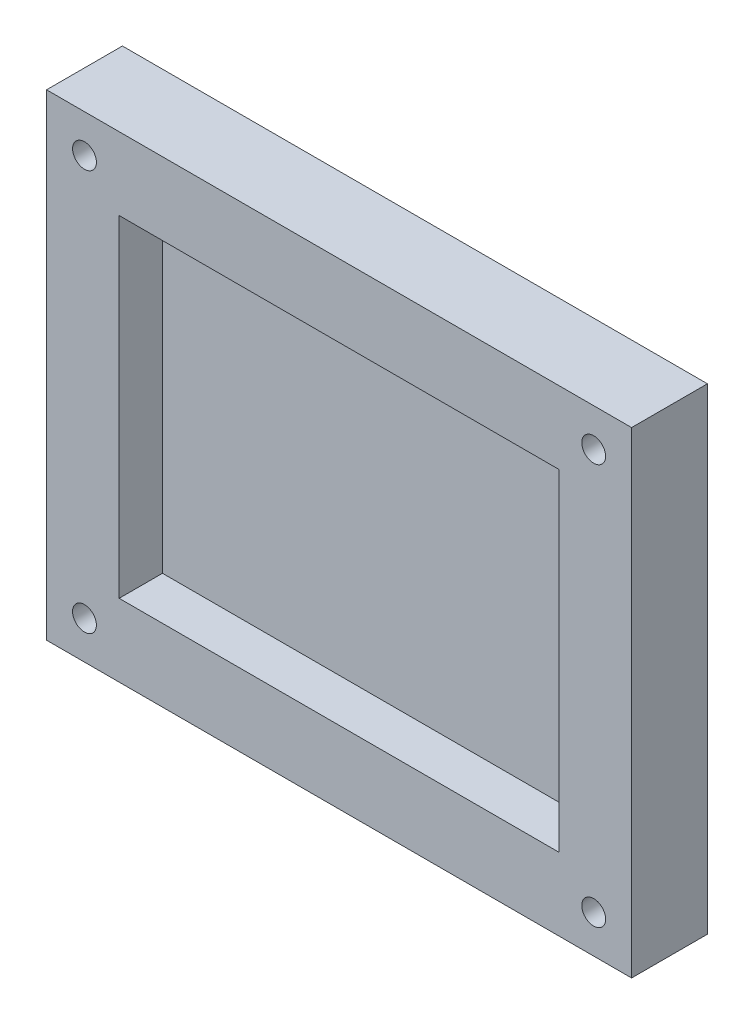
SolidWorks part; units mm, degrees
ref_plane "Front Plane" through (0, 0, 0) normal (0, 0, 1) x (1, 0, 0)
ref_plane "Top Plane" through (0, 0, 0) normal (0, 1, 0) x (1, 0, 0)
ref_plane "Right Plane" through (0, 0, 0) normal (1, 0, 0) x (0, 0, -1)
other "Configuration Table"
sketch "Sketch2" plane through (0, 0, 0) normal (0, 0, 1) x (1, 0, 0)
  line L1 (-54, -44) -> (54, -44)
  line L2 (-54, -44) -> (-54, 44)
  line L3 (-54, 44) -> (54, 44)
  line L4 (54, -44) -> (54, 44)
extrude "Fixture_floor" add sketch "Sketch2" along normal blind 6 from offset 0
sketch "Sketch3" plane through (0, 0, 0) normal (0, 0, 1) x (1, 0, 0)
  line L1 (-54, -44) -> (54, -44)
  line L2 (-54, -44) -> (-54, 44)
  line L3 (-54, 44) -> (54, 44)
  line L4 (54, -44) -> (54, 44)
  line L5 (-40.6, -30.6) -> (40.6, -30.6)
  line L6 (-40.6, -30.6) -> (-40.6, 30.6)
  line L7 (-40.6, 30.6) -> (40.6, 30.6)
  line L8 (40.6, -30.6) -> (40.6, 30.6)
extrude "Enclosure_nest" add sketch "Sketch3" along normal blind 8 from offset 6
sketch "Sketch4" plane through (0, 0, 0) normal (0, 0, 1) x (1, 0, 0)
  circle A0 centre (-47, -37) radius 2.2
extrude "Bench_mount_clearance" cut sketch "Sketch4" along normal blind 14 from offset 0
sketch "Sketch5" plane through (0, 0, 0) normal (0, 0, 1) x (1, 0, 0)
  circle A0 centre (-47, 37) radius 2.2
extrude "Cut-Extrude2" cut sketch "Sketch5" along normal blind 14 from offset 0
sketch "Sketch6" plane through (0, 0, 0) normal (0, 0, 1) x (1, 0, 0)
  circle A0 centre (47, -37) radius 2.2
extrude "Cut-Extrude3" cut sketch "Sketch6" along normal blind 14 from offset 0
sketch "Sketch7" plane through (0, 0, 0) normal (0, 0, 1) x (1, 0, 0)
  circle A0 centre (47, 37) radius 2.2
extrude "Cut-Extrude4" cut sketch "Sketch7" along normal blind 14 from offset 0
